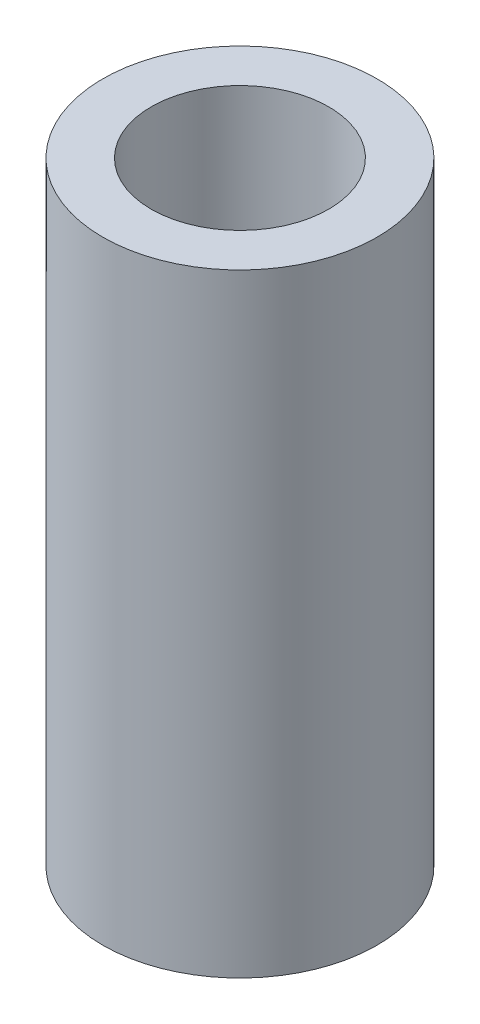
SolidWorks part; units mm, degrees
material "ABS"
ref_plane "前视基准面" through (0, 0, 0) normal (0, 0, 1) x (1, 0, 0)
ref_plane "上视基准面" through (0, 0, 0) normal (0, 1, 0) x (1, 0, 0)
ref_plane "右视基准面" through (0, 0, 0) normal (1, 0, 0) x (0, 0, -1)
other "Configuration Table"
sketch "草图1" plane through (0, 0, 0) normal (0, 1, 0) x (1, 0, 0)
  circle A0 centre (0, 0) radius 2.75
  circle A1 centre (0, 0) radius 4.25
  dimension "D1" = 5.5
  dimension "D2" = 8.5
extrude "凸台-拉伸1" add sketch "草图1" along normal blind 19
